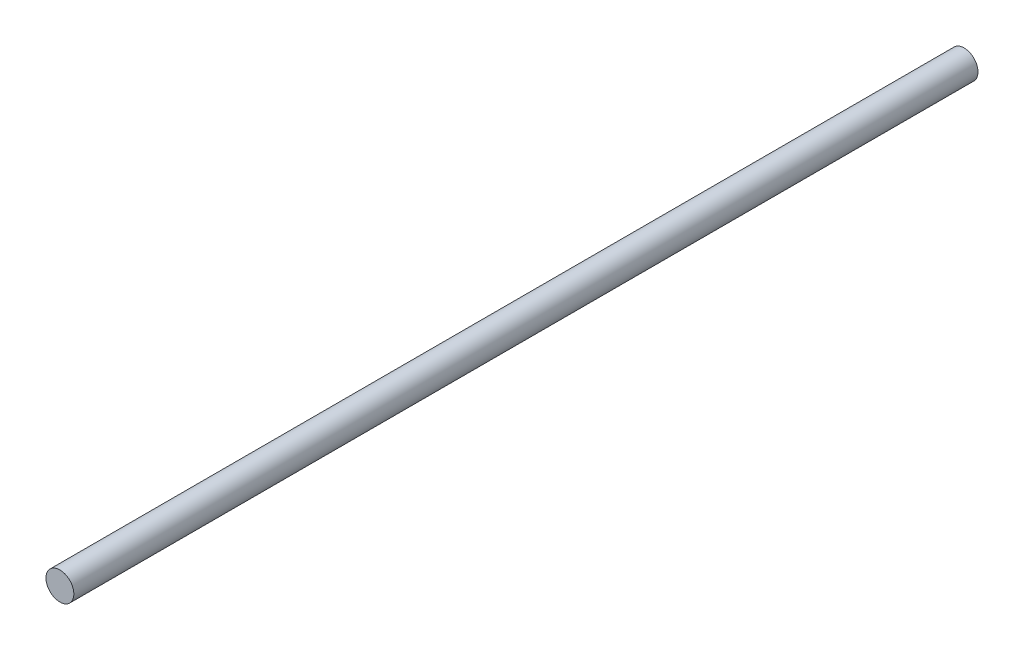
SolidWorks part; units mm, degrees
ref_plane "Plano frontal" through (0, 0, 0) normal (0, 0, 1) x (1, 0, 0)
ref_plane "Plano superior" through (0, 0, 0) normal (0, 1, 0) x (1, 0, 0)
ref_plane "Plano direito" through (0, 0, 0) normal (1, 0, 0) x (0, 0, -1)
sketch "Esboço1" plane through (0, 0, 0) normal (0, 0, 1) x (1, 0, 0)
  circle A0 centre (0, 0) radius 3
  dimension "D1" = 6
extrude "Ressalto-extrusão1" add sketch "Esboço1" along normal blind 194.8
